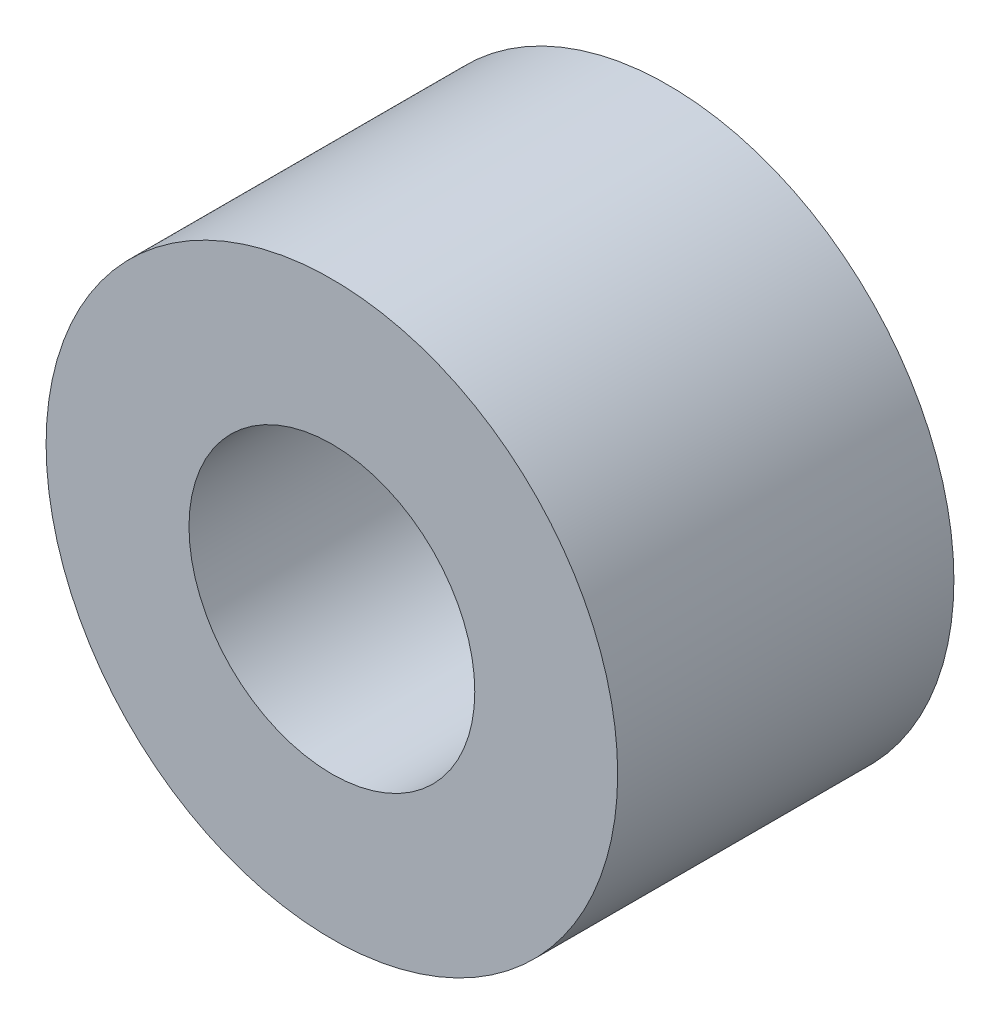
SolidWorks part; units mm, degrees
ref_plane "Front" through (0, 0, 0) normal (0, 0, 1) x (1, 0, 0)
ref_plane "Top" through (0, 0, 0) normal (0, 1, 0) x (1, 0, 0)
ref_plane "Right" through (0, 0, 0) normal (1, 0, 0) x (0, 0, -1)
sketch "Esquisse1" plane through (0, 0, 0) normal (0, 0, 1) x (1, 0, 0)
  circle A0 centre (0, 0) radius 4.25
  circle A1 centre (0, 0) radius 8.5
  dimension "D1" = 8.5
  dimension "D2" = 17
extrude "Boss.-Extru.1" add sketch "Esquisse1" along normal blind 10
